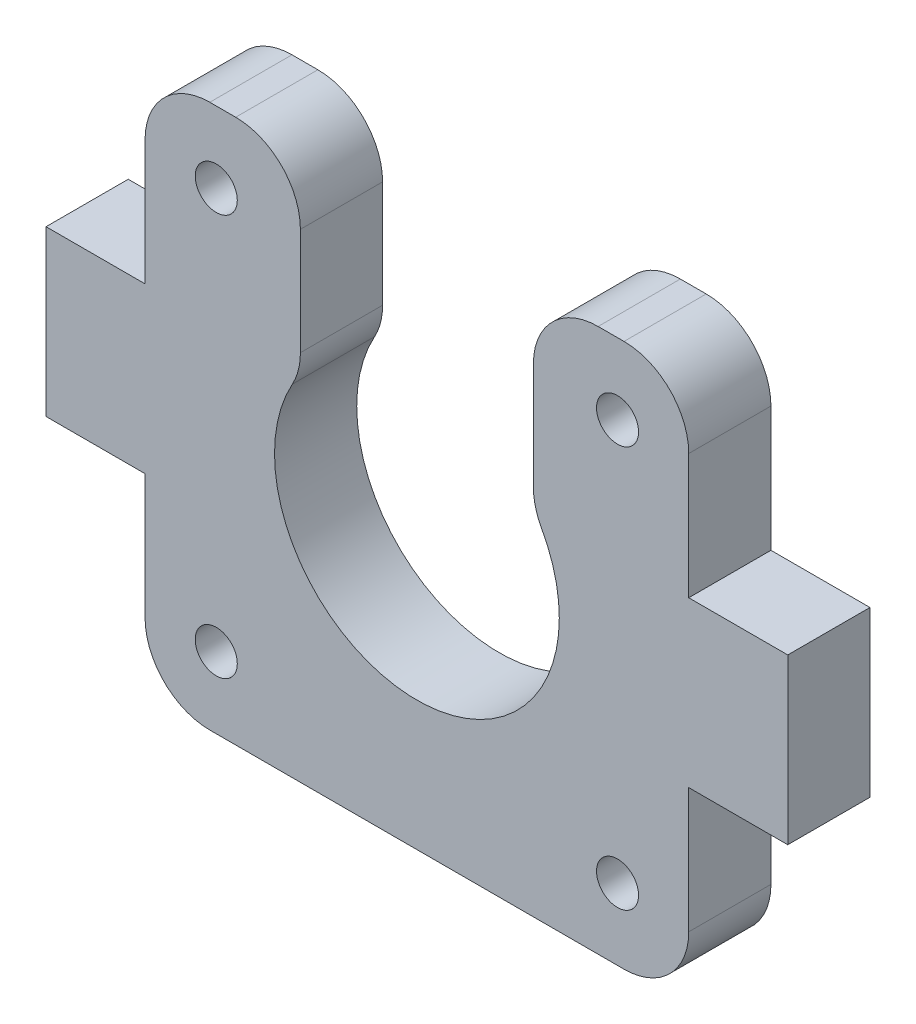
SolidWorks part; units mm, degrees
ref_plane "Front Plane" through (0, 0, 0) normal (0, 0, 1) x (1, 0, 0)
ref_plane "Top Plane" through (0, 0, 0) normal (0, 1, 0) x (1, 0, 0)
ref_plane "Right Plane" through (0, 0, 0) normal (1, 0, 0) x (0, 0, -1)
sketch "Sketch1" plane through (0, 0, 0) normal (0, 0, 1) x (1, 0, 0)
  line L1 (28.65, -21) -> (-28.65, -21)
  line L2 (28.65, -21) -> (28.65, 21)
  line L3 (28.65, 21) -> (-28.65, 21)
  line L4 (-28.65, -21) -> (-28.65, 21)
  line L5 (28.65, -21) -> (-28.65, 21) construction
  line L6 (28.65, 21) -> (-28.65, -21) construction
  point P0 (0, 0)
  dimension "D1" = 57.3
  dimension "D2" = 42
extrude "Boss-Extrude1" add sketch "Sketch1" along normal blind 6.35
hole_wizard "Tap Drill for M3x0.5 Tap1" positions "Sketch2" profile "Sketch3" hole size "M3x0.5" standard "ANSI Metric" end condition up to next
sketch "Sketch2" plane through (0, 0, 6.35) normal (0, 0, 1) x (1, 0, 0)
  line L0 (-15.5, 15.5) -> (15.5, 15.5) construction
  line L1 (15.5, 15.5) -> (15.5, -15.5) construction
  line L2 (15.5, -15.5) -> (-15.5, -15.5) construction
  line L3 (-15.5, -15.5) -> (-15.5, 15.5) construction
  line L4 (-15.5, 15.5) -> (15.5, -15.5) construction
  line L5 (15.5, -15.5) -> (-15.5, -15.5) construction
  line L6 (-15.5, -15.5) -> (15.5, 15.5) construction
  point P0 (15.5, 15.5)
  point P2 (15.5, -15.5)
  point P4 (-15.5, 15.5)
  point P6 (-15.5, -15.5)
  point P24 (0, 0)
  dimension "D1" = 31
sketch "Sketch3" plane through (15.5, 15.5, 6.35) normal (1, 0, 0) x (0, -1, 0)
  line L0 (0, 0) -> (0, 6.35)
  line L1 (0, 6.35) -> (1.625, 6.35)
  line L2 (1.625, 6.35) -> (1.625, 0)
  line L5 (1.625, 0) -> (0, 0)
  line L11 (0, -6.35) -> (0, 107.95) construction
  dimension "Thru Hole Dia." = 3.25
  dimension "Thru Hole Depth" = 6.35
sketch "Sketch4" plane through (0, 0, 6.35) normal (0, 0, 1) x (1, 0, 0)
  line L0 (28.65, 21) -> (-28.65, 21) construction
  line L1 (9, 6.3246) -> (-9, 6.3246)
  line L2 (9, 6.3246) -> (9, 21)
  line L3 (9, 21) -> (-9, 21)
  line L4 (-9, 6.3246) -> (-9, 21)
  line L5 (9, 6.3246) -> (-9, 21) construction
  line L6 (9, 21) -> (-9, 6.3246) construction
  circle A0 centre (0, 0) radius 11
  point P3 (0, 13.6623)
  line M8 (28.65, 21) -> (-28.65, 21)
  dimension "D1" = 22
  dimension "D2" = 18
extrude "Cut-Extrude1" cut sketch "Sketch4" against normal through all contours L1 A0 | A0 L2 L4 M8 | L1 A0
sketch "Sketch5" plane through (0, 0, 6.35) normal (0, 0, 1) x (1, 0, 0)
  line L0 (-28.65, 21) -> (-28.65, -21) construction
  line L1 (-21, 6.35) -> (-28.65, 6.35)
  line L2 (-21, 6.35) -> (-21, 21)
  line L3 (-21, 21) -> (-28.65, 21)
  line L4 (-28.65, 6.35) -> (-28.65, 21)
  line L5 (-21, 6.35) -> (-28.65, 21) construction
  line L6 (-21, 21) -> (-28.65, 6.35) construction
  line L9 (-28.65, -21) -> (28.65, -21) construction
  line L10 (-28.65, 21) -> (-28.65, -21) construction
  line L11 (-28.65, -6.35) -> (-21, -6.35)
  line L12 (-28.65, -6.35) -> (-28.65, -21)
  line L13 (-28.65, -21) -> (-21, -21)
  line L14 (-21, -6.35) -> (-21, -21)
  line L15 (-28.65, -6.35) -> (-21, -21) construction
  line L16 (-28.65, -21) -> (-21, -6.35) construction
  line L17 (-21, -6.35) -> (-21, 6.35) construction
  line L18 (-9, 21) -> (-28.65, 21) construction
  point P0 (-24.825, 13.675)
  point P9 (-21, 0)
  point P12 (-24.825, -13.675)
  dimension "D1" = 12.7
  dimension "D2" = 21
extrude "Cut-Extrude2" cut sketch "Sketch5" against normal through all
mirror "Mirror1" about plane through (0, 0, 0) normal (1, 0, 0) of "Cut-Extrude2"
fillet "Fillet1" radius 5 8 edges at (9, 21, 3.175) (-9, 21, 3.175) (-9, 6.3246, 3.175) (9, 6.3246, 3.175) (-21, -21, 3.175) (21, -21, 3.175) (21, 21, 3.175) (-21, 21, 3.175)
